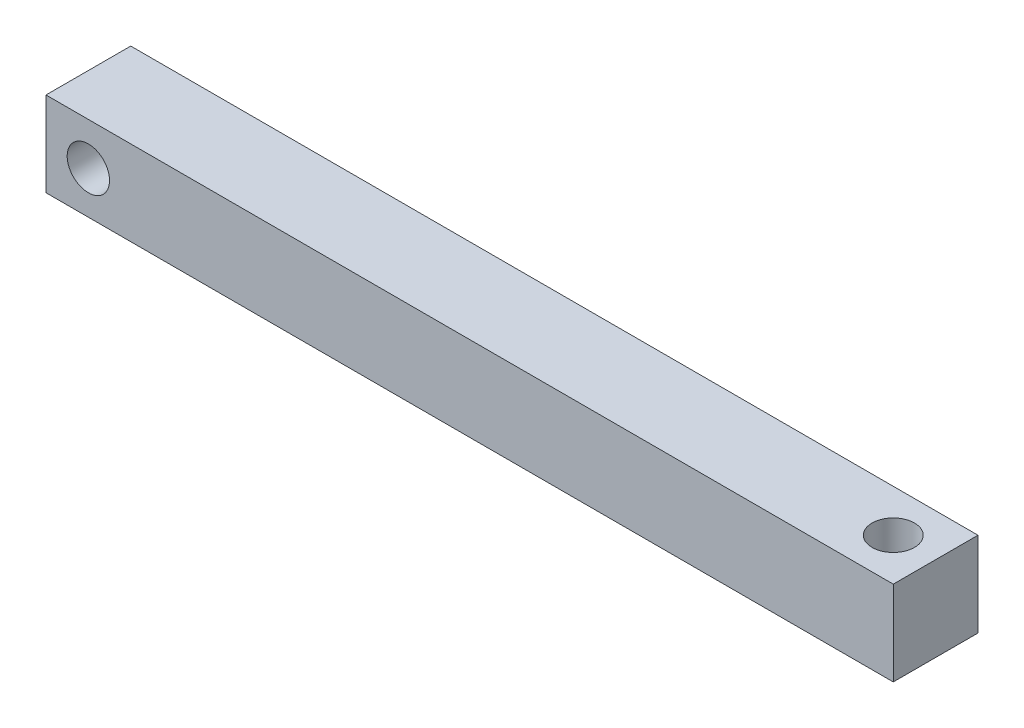
SolidWorks part; units mm, degrees
ref_plane "Front Plane" through (0, 0, 0) normal (0, 0, 1) x (1, 0, 0)
ref_plane "Top Plane" through (0, 0, 0) normal (0, 1, 0) x (1, 0, 0)
ref_plane "Right Plane" through (0, 0, 0) normal (1, 0, 0) x (0, 0, -1)
sketch "Sketch1" plane through (0, 0, 0) normal (0, 0, 1) x (1, 0, 0)
  line L1 (-100, 10) -> (100, 10)
  line L2 (-100, 10) -> (-100, -10)
  line L3 (-100, -10) -> (100, -10)
  line L4 (100, 10) -> (100, -10)
  line L5 (-100, 10) -> (100, -10) construction
  line L6 (-100, -10) -> (100, 10) construction
  point P0 (0, 0)
  dimension "D1" = 200
  dimension "D2" = 20
extrude "Boss-Extrude2" add sketch "Sketch1" along normal blind 20
sketch "Sketch3" plane through (0, 0, 20) normal (0, 0, 1) x (1, 0, 0)
  line L0 (-100, 10) -> (-100, -10) construction
  line L1 (-100, -10) -> (100, -10) construction
  circle A0 centre (-90, 0) radius 5
  dimension "D1" = 10
  dimension "D2" = 10
  dimension "D3" = 10
extrude "Cut-Extrude1" cut sketch "Sketch3" against normal through all
sketch "Sketch4" plane through (0, -10, 0) normal (0, -1, 0) x (1, 0, 0)
  line L0 (100, 20) -> (100, 0) construction
  line L1 (-100, 0) -> (100, 0) construction
  circle A0 centre (90, 10) radius 5
  dimension "D1" = 10
  dimension "D2" = 10
  dimension "D3" = 10
extrude "Cut-Extrude2" cut sketch "Sketch4" against normal through all
equation "\"segment width\" = 60"
equation "\"segment support width\"= 20"
equation "\"servo hole\"= 10'arbitrary atm"
equation "\"segment length 1\"= 200"
equation "\"segment length 2\"= 200"
equation "\"segment length 3\"= 200"
equation "\"segment length 4\"= 100"
equation "\"segment length 5\"= 100"
equation "\"base diameter\"= 100"
equation "\"base height\"= 50"
equation "\"D1@Sketch1\"= \"segment length 2\""
equation "\"D2@Sketch1\"=\"segment support width\""
equation "\"D1@Boss-Extrude2\"=\"segment support width\""
equation "\"D1@Sketch3\"=\"servo hole\""
equation "\"D2@Sketch3\"=\"segment support width\"/2"
equation "\"D3@Sketch3\"=\"segment support width\"/2"
equation "\"D1@Sketch4\"=\"servo hole\""
equation "\"D2@Sketch4\"=\"servo hole\""
equation "\"D3@Sketch4\"=\"servo hole\""
